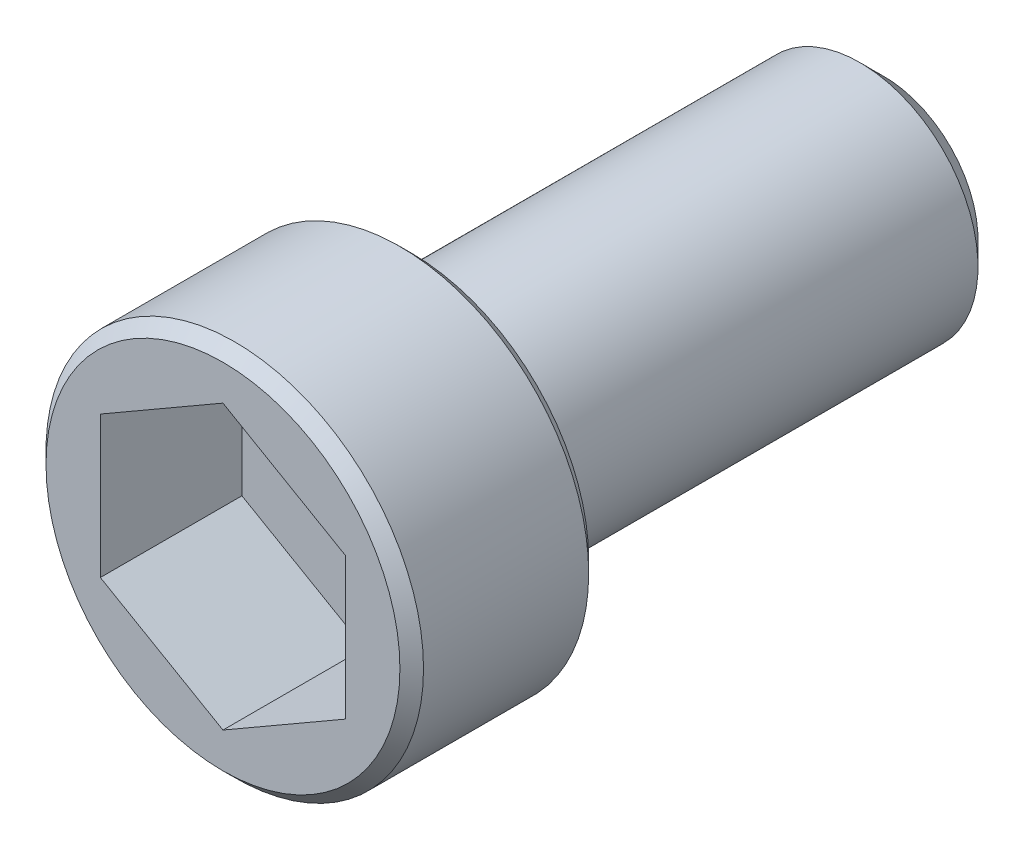
SolidWorks part; units mm, degrees
ref_plane "Front Plane" through (0, 0, 0) normal (1, 0, 0) x (0, 1, 0)
ref_plane "Top Plane" through (0, 0, 0) normal (0, 0, 1) x (0, 1, 0)
ref_plane "Right Plane" through (0, 0, 0) normal (0, 1, 0) x (-1, 0, 0)
sketch "Sketch1" plane through (0, 0, 0) normal (0, 0, 1) x (0, 1, 0)
  circle A0 centre (0, 0) radius 4
  dimension "D1" = 8
extrude "Boss-Extrude1" add sketch "Sketch1" against normal blind 4
chamfer "Chamfer1" distance 0.25 angle 45 2 edges at (4, 0, -4) (4, 0, 0)
sketch "Sketch2" plane through (0, 0, 0) normal (0, 0, 1) x (1, 0, 0)
  line L1 (0, 3) -> (-2.5981, 1.5)
  line L2 (-2.5981, 1.5) -> (-2.5981, -1.5)
  line L3 (-2.5981, -1.5) -> (0, -3)
  line L4 (0, -3) -> (2.5981, -1.5)
  line L5 (2.5981, -1.5) -> (2.5981, 1.5)
  line L6 (2.5981, 1.5) -> (0, 3)
  circle A0 centre (0, 0) radius 2.5981 construction
  dimension "D1" = 3
  dimension "D2" = 2.5981
extrude "Cut-Extrude1" cut sketch "Sketch2" against normal blind 3
sketch "Sketch3" plane through (0, 0, -4) normal (0, 0, -1) x (1, 0, 0)
  circle A0 centre (0, 0) radius 2.5
  dimension "D1" = 5
extrude "Boss-Extrude2" add sketch "Sketch3" along normal blind 10
chamfer "Chamfer2" distance 0.5 angle 45 1 edges at (-2.5, 0, -14)
